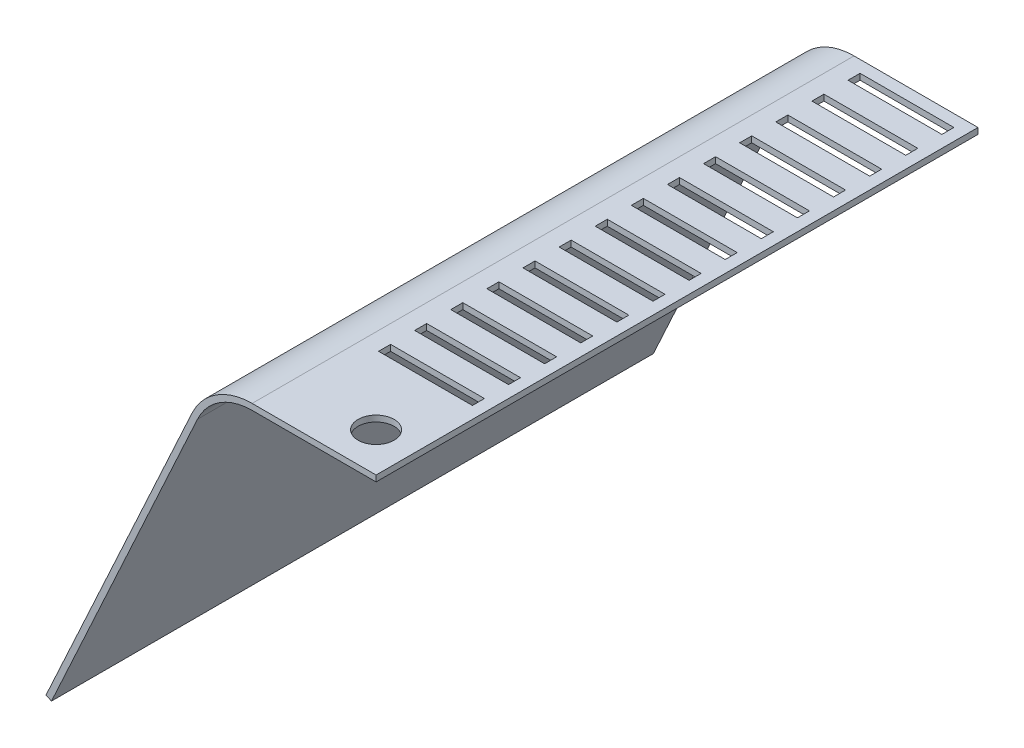
SolidWorks part; units mm, degrees
ref_plane "Front Plane" through (0, 0, 0) normal (0, 0, 1) x (1, 0, 0)
ref_plane "Top Plane" through (0, 0, 0) normal (0, 1, 0) x (1, 0, 0)
ref_plane "Right Plane" through (0, 0, 0) normal (1, 0, 0) x (0, 0, -1)
sketch "Sketch1" plane through (0, 0, 0) normal (0, 0, 1) x (1, 0, 0)
  line L0 (0, 0) -> (-205.95, 0)
  line L1 (-296.7862, -58.1816) -> (-539.333, -585.0317)
  arc A0 (-205.95, 0) -> (-296.7862, -58.1816) centre (-205.95, -100) ccw
  point P6 (-31.7091, 0)
  point P7 (-151.977, -117.1921)
  point P8 (-194.84, -197.8157)
  point P9 (-235.9812, -55.1072)
  dimension "D1" = 100
  dimension "D2" = 205.95
  dimension "D3" = 114.72
  dimension "D4" = 580
extrude "Extrude-Thin1" add sketch "Sketch1" along normal mid plane 1000 thin
sketch "Sketch2" plane through (0, 10, 0) normal (0, 1, 0) x (1, 0, 0)
  line L0 (0, -500) -> (0, 500) construction
  line L1 (-175.95, 480) -> (-20, 480)
  line L2 (-175.95, 480) -> (-175.95, 460)
  line L3 (-175.95, 460) -> (-20, 460)
  line L4 (-20, 480) -> (-20, 460)
  line L5 (0, 500) -> (-205.95, 500) construction
  line L6 (-205.95, -500) -> (-205.95, 500) construction
  dimension "D1" = 20
  dimension "D2" = 20
  dimension "D3" = 20
  dimension "D4" = 30
extrude "Cut-Extrude1" cut sketch "Sketch2" against normal through all
pattern_linear "LPattern1" count 14 spacing 60 along (0, 0, 1) of "Cut-Extrude1"
sketch "Sketch3" plane through (0, 10, 0) normal (0, 1, 0) x (1, 0, 0)
  line L0 (0, -500) -> (-205.95, -500) construction
  line L1 (0, -500) -> (0, 500) construction
  circle A0 centre (-65, -435) radius 30
  dimension "D3" = 60
  dimension "D1" = 65
  dimension "D2" = 65
extrude "Cut-Extrude2" cut sketch "Sketch3" against normal through all
